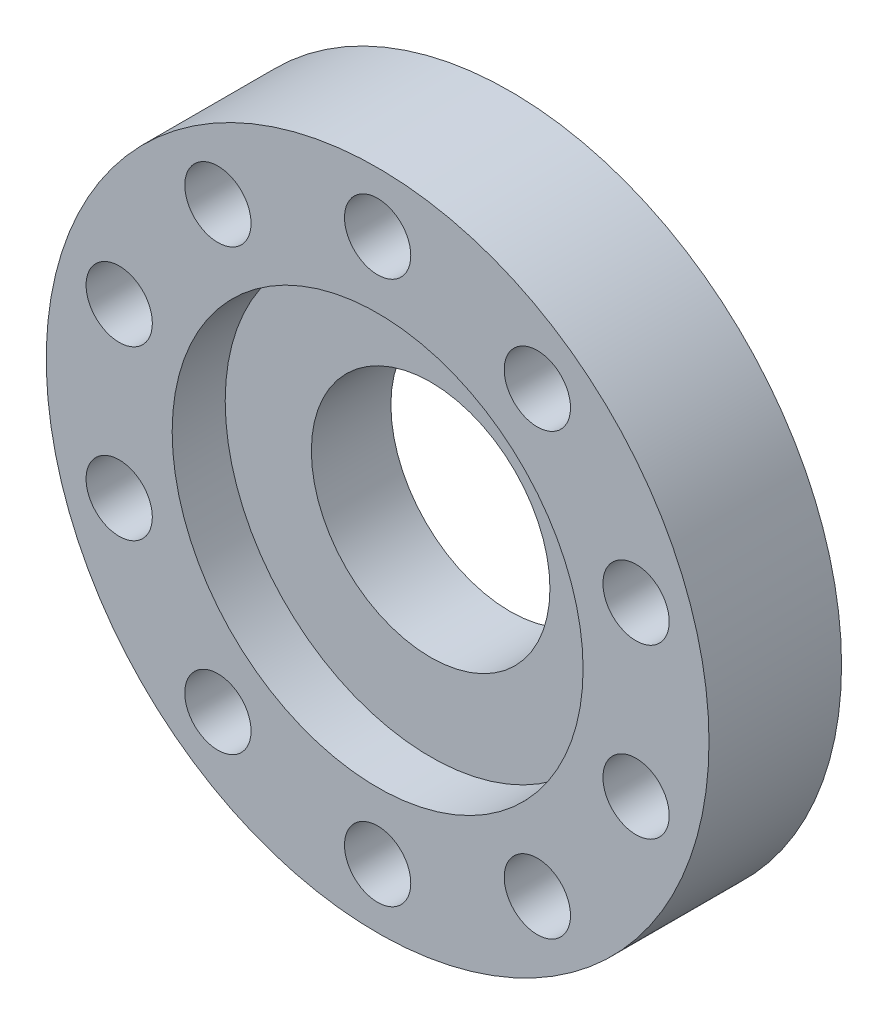
SolidWorks part; units mm, degrees
material "1.0050 (E295)"
ref_plane "Front Plane" through (0, 0, 0) normal (0, 0, 1) x (1, 0, 0)
ref_plane "Top Plane" through (0, 0, 0) normal (0, 1, 0) x (1, 0, 0)
ref_plane "Right Plane" through (0, 0, 0) normal (1, 0, 0) x (0, 0, -1)
sketch "Sketch1" plane through (0, 0, 0) normal (0, 0, 1) x (1, 0, 0)
  circle A0 centre (0, 0) radius 50
  circle A2 centre (0, 0) radius 41 construction
  circle A3 centre (0, 0) radius 18
  circle A4 centre (0, -41) radius 5
  circle A5 centre (-24.0992, -33.1697) radius 5
  circle A6 centre (-38.9933, -12.6697) radius 5
  circle A7 centre (-38.9933, 12.6697) radius 5
  circle A8 centre (-24.0992, 33.1697) radius 5
  circle A9 centre (0, 41) radius 5
  circle A10 centre (24.0992, 33.1697) radius 5
  circle A11 centre (38.9933, 12.6697) radius 5
  circle A12 centre (38.9933, -12.6697) radius 5
  circle A13 centre (24.0992, -33.1697) radius 5
  point P28 (0, 0)
  dimension "D1" = 100
  dimension "D2" = 82
  dimension "D3" = 36
  dimension "D4" = 10
  dimension "D5" = 10
extrude "Boss-Extrude1" add sketch "Sketch1" along normal blind 20
sketch "Sketch2" plane through (0, 0, 20) normal (0, 0, 1) x (1, 0, 0)
  circle A0 centre (0, 0) radius 31
  circle A1 centre (0, 0) radius 18 construction
  circle A2 centre (0, 0) radius 18
  dimension "D1" = 62
extrude "Cut-Extrude1" cut sketch "Sketch2" against normal blind 8
